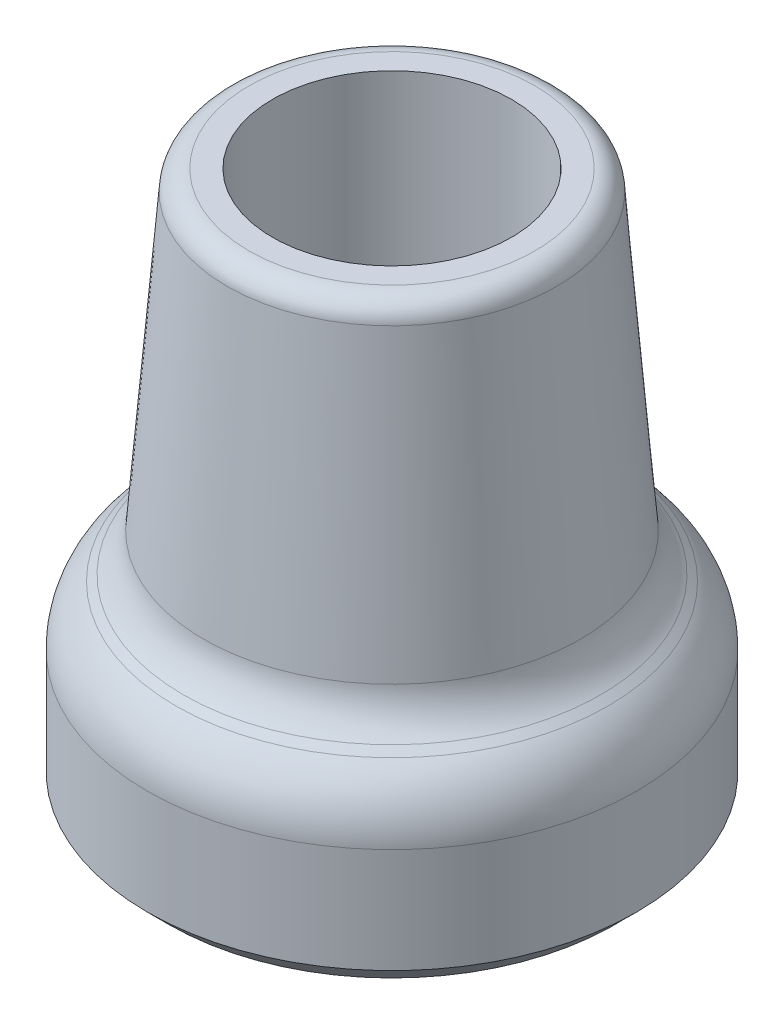
SolidWorks part; units mm, degrees
material "Резина"
ref_plane "Спереди" through (0, 0, 0) normal (0, 0, 1) x (1, 0, 0)
ref_plane "Сверху" through (0, 0, 0) normal (0, 1, 0) x (1, 0, 0)
ref_plane "Справа" through (0, 0, 0) normal (1, 0, 0) x (0, 0, -1)
sketch "Эскиз1" plane through (0, 0, 0) normal (0, 0, 1) x (1, 0, 0)
  line L0 (0, 0) -> (0, 173.285) construction
  line L1 (0, 20) -> (-11, 20)
  line L2 (-11, 20) -> (-11, 50)
  line L3 (-11, 50) -> (-15, 50)
  line L4 (-15, 50) -> (-17.5, 19)
  line L5 (-17.5, 19) -> (-22.5, 15)
  line L6 (-22.5, 15) -> (-22.5, 0)
  line L7 (-22.5, 0) -> (0, 0)
  line L8 (0, 0) -> (0, 20)
  dimension "D1" = 22
  dimension "D2" = 30
  dimension "D3" = 15
  dimension "D4" = 45
  dimension "D5" = 30
  dimension "D6" = 35
  dimension "D7" = 4
  dimension "D8" = 50
revolve "Повернуть1" add sketch "Эскиз1" angle 360 about L0
fillet "Скругление1" radius 2 1 edges at (0, 50, -15)
fillet "Скругление2" radius 5 1 edges at (0, 19, -17.5)
fillet "Скругление3" radius 7 1 edges at (0, 15, -22.5)
chamfer "Фаска1" distance 2 angle 45 1 edges at (0, 0, -22.5)
fillet "Скругление4" radius 1 1 edges at (0, 20, -11)
